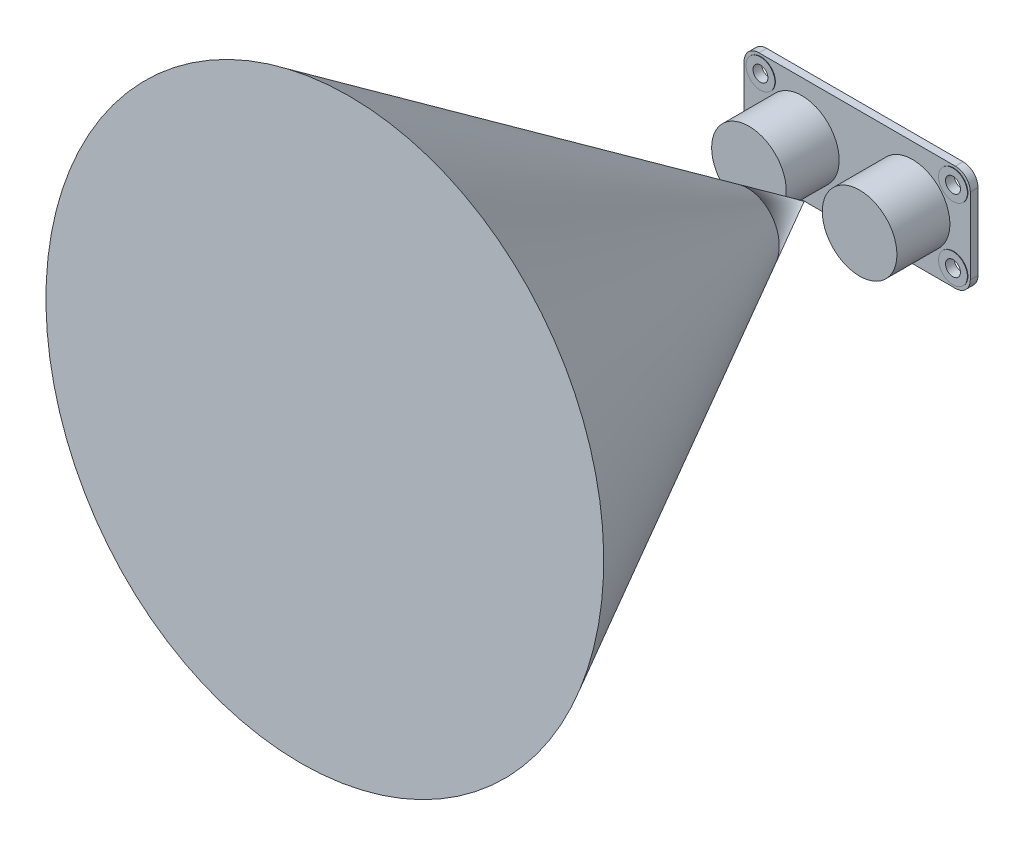
SolidWorks part; units mm, degrees
ref_plane "Front Plane" through (0, 0, 0) normal (0, 0, 1) x (1, 0, 0)
ref_plane "Top Plane" through (0, 0, 0) normal (0, 1, 0) x (1, 0, 0)
ref_plane "Right Plane" through (0, 0, 0) normal (1, 0, 0) x (0, 0, -1)
sketch "Sketch1" plane through (0, 0, 0) normal (0, 0, 1) x (1, 0, 0)
  line L1 (-23.5, -11) -> (23.5, -11)
  line L2 (-23.5, -11) -> (-23.5, 11)
  line L3 (-23.5, 11) -> (23.5, 11)
  line L4 (23.5, -11) -> (23.5, 11)
  line L5 (-23.5, -11) -> (23.5, 11) construction
  line L6 (-23.5, 11) -> (23.5, -11) construction
  circle A0 centre (-20, 7.5) radius 1.55
  circle A1 centre (20, 7.5) radius 1.55
  circle A2 centre (20, -7.5) radius 1.55
  circle A3 centre (-20, -7.5) radius 1.55
  point P0 (0, 0)
  dimension "D3" = 40
  dimension "D5" = 3.1
  dimension "D6" = 3.1
  dimension "D7" = 3.1
  dimension "D8" = 3.1
  dimension "D1" = 47
  dimension "D2" = 22
  dimension "D4" = 15
  dimension "D9" = 7.5
  dimension "D10" = 20
extrude "Boss-Extrude1" add sketch "Sketch1" along normal blind 1.6
fillet "Fillet1" radius 3.1 4 edges at (-23.5, 11, 0.8) (-23.5, -11, 0.8) (23.5, -11, 0.8) (23.5, 11, 0.8)
sketch "Sketch2" plane through (0, 0, 1.6) normal (0, 0, 1) x (1, 0, 0)
  circle A0 centre (-20, 7.5) radius 3
  circle A1 centre (-20, -7.5) radius 3
  circle A2 centre (20, 7.5) radius 3
  circle A3 centre (20, -7.5) radius 3
  circle A4 centre (-20, 7.5) radius 1.55
  circle A5 centre (20, 7.5) radius 1.55
  circle A6 centre (20, -7.5) radius 1.55
  circle A7 centre (-20, -7.5) radius 1.55
  dimension "D1" = 6
  dimension "D2" = 6
  dimension "D3" = 6
  dimension "D4" = 6
  dimension "D5" = 3.1
  dimension "D6" = 3.1
  dimension "D7" = 3.1
  dimension "D8" = 3.1
extrude "Boss-Extrude4" add sketch "Sketch2" along normal blind 0.1 and the other way blind 1.7
sketch "Sketch3" plane through (0, 0, 1.6) normal (0, 0, 1) x (1, 0, 0)
  line L0 (-20.4, -11) -> (20.4, -11) construction
  circle A0 centre (11.5, 0) radius 7.75
  circle A1 centre (-11.5, 0) radius 7.75
  dimension "D1" = 15.5
  dimension "D2" = 15.5
  dimension "D5" = 11
  dimension "D6" = 11
  dimension "D3" = 23
  dimension "D4" = 11.5
extrude "Boss-Extrude8" add sketch "Sketch3" along normal blind 11
sketch "Sketch7" plane through (0, 0, 0) normal (1, 0, 0) x (0, 0, -1)
  line L0 (-12.6, 0) -> (-107.1875, 66.2309)
  line L2 (-12.6, 7.75) -> (-12.6, -7.75) construction
  line L3 (-107.1875, 66.2309) -> (-112.2195, 8.7156)
  line L6 (-12.6, 0) -> (-112.2195, 8.7156)
  line L8 (-12.6, -7.75) -> (-1.6, -7.75) construction
  point P4 (-112.6, 8.5965)
  dimension "D1" = 30
  dimension "D2" = 5
  dimension "D3" = 100
revolve "Revolve1" add sketch "Sketch7" angle 360 about L6
